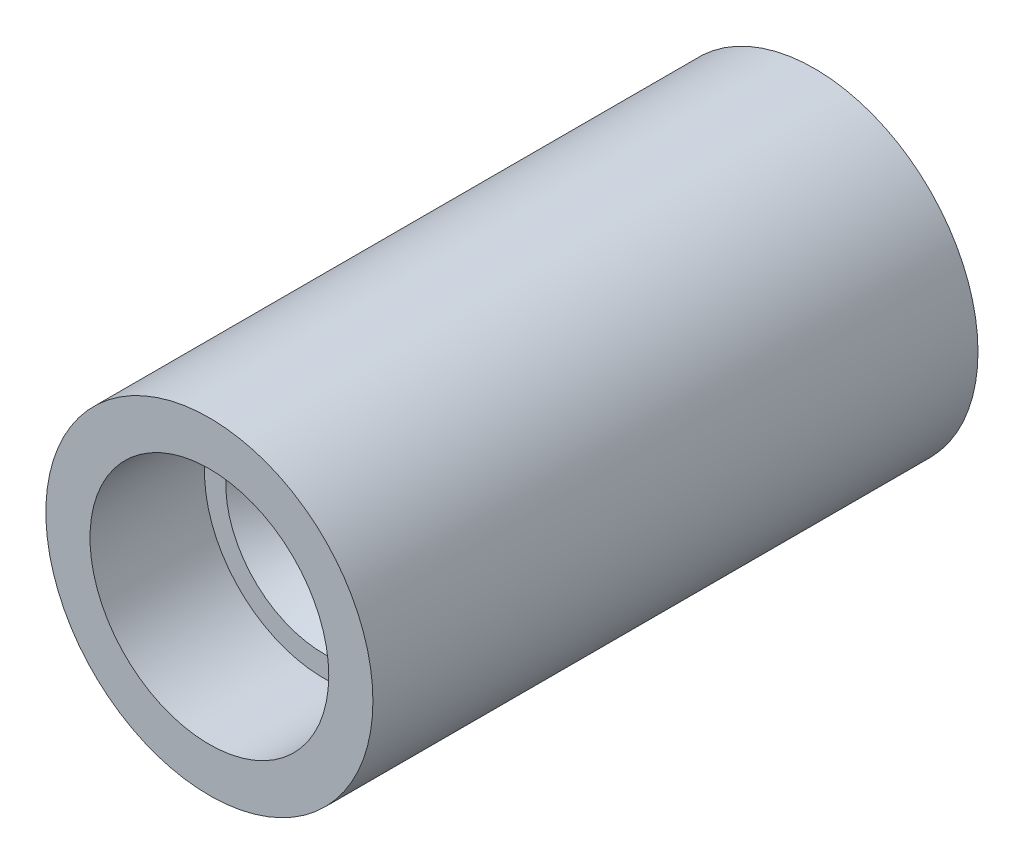
SolidWorks part; units mm, degrees
ref_plane "Front Plane" through (0, 0, 0) normal (0, 0, 1) x (1, 0, 0)
ref_plane "Top Plane" through (0, 0, 0) normal (0, 1, 0) x (1, 0, 0)
ref_plane "Right Plane" through (0, 0, 0) normal (1, 0, 0) x (0, 0, -1)
sketch "Sketch1" plane through (0, 0, 0) normal (0, 0, 1) x (1, 0, 0)
  circle A0 centre (0, 0) radius 5
  dimension "D1" = 10
extrude "Boss-Extrude1" add sketch "Sketch1" along normal blind 18.5
sketch "Sketch2" plane through (0, 0, 18.5) normal (0, 0, 1) x (1, 0, 0)
  circle A0 centre (0, 0) radius 2
  dimension "D1" = 4
extrude "Cut-Extrude1" cut sketch "Sketch2" against normal up to surface (18.5 mm away) up to face at (5, 0, 0)
sketch "Sketch3" plane through (0, 0, 18.5) normal (0, 0, 1) x (1, 0, 0)
  circle A0 centre (0, 0) radius 3.65
  dimension "D1" = 7.3
extrude "Cut-Extrude2" cut sketch "Sketch3" against normal blind 3.5
sketch "Sketch4" plane through (0, 0, 0) normal (0, 0, -1) x (-1, 0, 0)
  circle A0 centre (0, 0) radius 3.65
  dimension "D1" = 7.3
extrude "Cut-Extrude3" cut sketch "Sketch4" against normal offset from surface (10.5 mm away) 8 up to face at (3.65, 0, 18.5)
chamfer "Chamfer1" distance 1.5 angle 45 1 edges at (2, 0, 10.5)
chamfer "Chamfer2" distance 1 angle 45 1 edges at (2, 0, 15)
sketch "Sketch5" plane through (0, 0, 0) normal (0, 0, -1) x (-1, 0, 0)
  line L1 (0, 4.2147) -> (-3.65, 2.1073)
  line L2 (-3.65, 2.1073) -> (-3.65, -2.1073)
  line L3 (-3.65, -2.1073) -> (0, -4.2147)
  line L4 (0, -4.2147) -> (3.65, -2.1073)
  line L5 (3.65, -2.1073) -> (3.65, 2.1073)
  line L6 (3.65, 2.1073) -> (0, 4.2147)
  circle A0 centre (0, 0) radius 3.65 construction
  circle A1 centre (0, 0) radius 3.65 construction
  point P11 (0, 4.2147)
  point P12 (0, 0)
extrude "Cut-Extrude4" cut sketch "Sketch5" against normal offset from surface (5 mm away) 5.5 up to face at (3.5, 0, 10.5)
